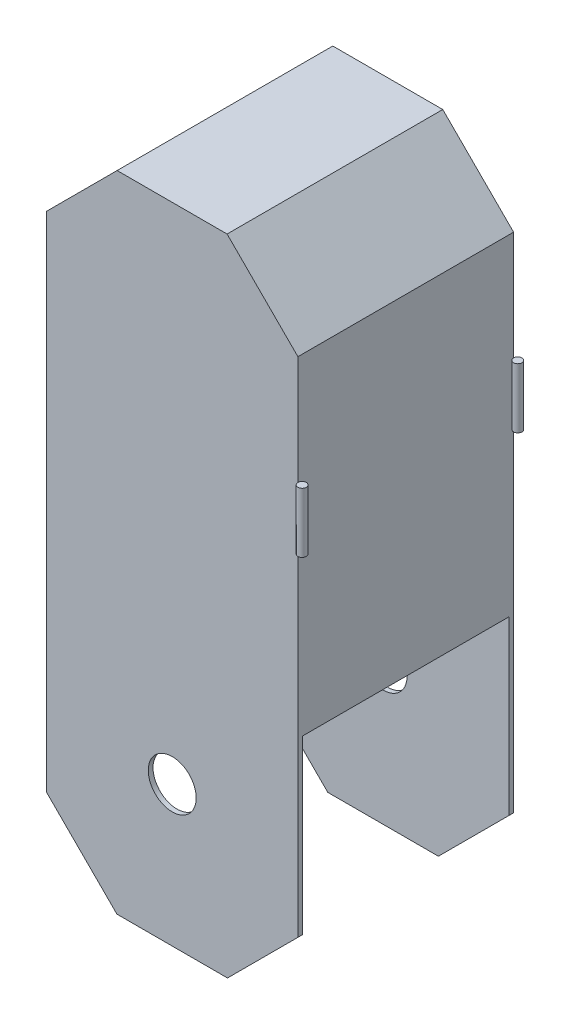
SolidWorks part; units mm, degrees
ref_plane "Спереди" through (0, 0, 0) normal (0, 0, 1) x (1, 0, 0)
ref_plane "Сверху" through (0, 0, 0) normal (0, 1, 0) x (1, 0, 0)
ref_plane "Справа" through (0, 0, 0) normal (1, 0, 0) x (0, 0, -1)
sketch "Эскиз1" plane through (0, 0, 0) normal (0, 0, 1) x (1, 0, 0)
  line L0 (105.0829, 581.7221) -> (45.979, 640.8259)
  line L1 (45.979, 640.8259) -> (-45.8132, 640.8259)
  line L2 (-45.8132, 640.8259) -> (-104.9171, 581.7221)
  line L3 (-104.9171, 581.7221) -> (-104.9171, 162.2129)
  line L4 (-104.9171, 162.2129) -> (-45.9732, 103.269)
  line L5 (-45.9732, 103.269) -> (46.3268, 103.269)
  line L6 (46.3268, 103.269) -> (105.0829, 162.0251)
  line L7 (105.0829, 162.0251) -> (105.0829, 581.7221)
  line L8 (0.0829, 640.8259) -> (0.0829, 703.4762) construction
  dimension "D1" = 105
  dimension "D2" = 105
extrude "Вытянуть1" add sketch "Эскиз1" along normal blind 180
sketch "Sketch1" plane through (105.0829, 0, 0) normal (1, 0, 0) x (0, 0, -1)
  line L0 (-248.5664, 317.269) -> (57.8162, 317.269) construction
  line L1 (-180, 103.269) -> (0, 103.269) construction
  line L2 (-180, 162.0251) -> (-180, 581.7221) construction
  line L3 (-176, 96.7638) -> (-4, 96.7638)
  line L4 (-176, 96.7638) -> (-176, 305.6262)
  line L5 (-176, 305.6262) -> (-4, 305.6262)
  line L6 (-4, 96.7638) -> (-4, 305.6262)
  line L7 (0, 162.0251) -> (0, 581.7221) construction
  dimension "D1" = 214
  dimension "D2" = 4
  dimension "D3" = 4
extrude "Cut-Extrude1" cut sketch "Sketch1" against normal through all
sketch "Sketch2" plane through (0, 0, 0) normal (0, 0, -1) x (-1, 0, 0)
  line L0 (45.9732, 103.269) -> (-46.3268, 103.269) construction
  circle A0 centre (-0.1768, 220.269) radius 20
  dimension "D1" = 117
extrude "Cut-Extrude2" cut sketch "Sketch2" against normal through all
ref_plane "Plane1" through (0, 440.8259, 0) normal (0, 1, 0) x (1, 0, 0)
sketch "Sketch3" plane through (0, 440.8259, 0) normal (0, 1, 0) x (1, 0, 0)
  line L0 (105.0829, 0) -> (156.2592, 51.1763) construction
  line L1 (-104.9171, 0) -> (-157.625, 0) construction
  line L2 (-104.9171, -90) -> (-175.894, -90) construction
  line L3 (105.0829, 0) -> (105.0829, 59.0755) construction
  circle A0 centre (108.5829, 0) radius 3.5
  circle A1 centre (108.5829, -180) radius 3.5
  dimension "D1" = 45
extrude "Boss-Extrude1" add sketch "Sketch3" along normal blind 50 separate body
